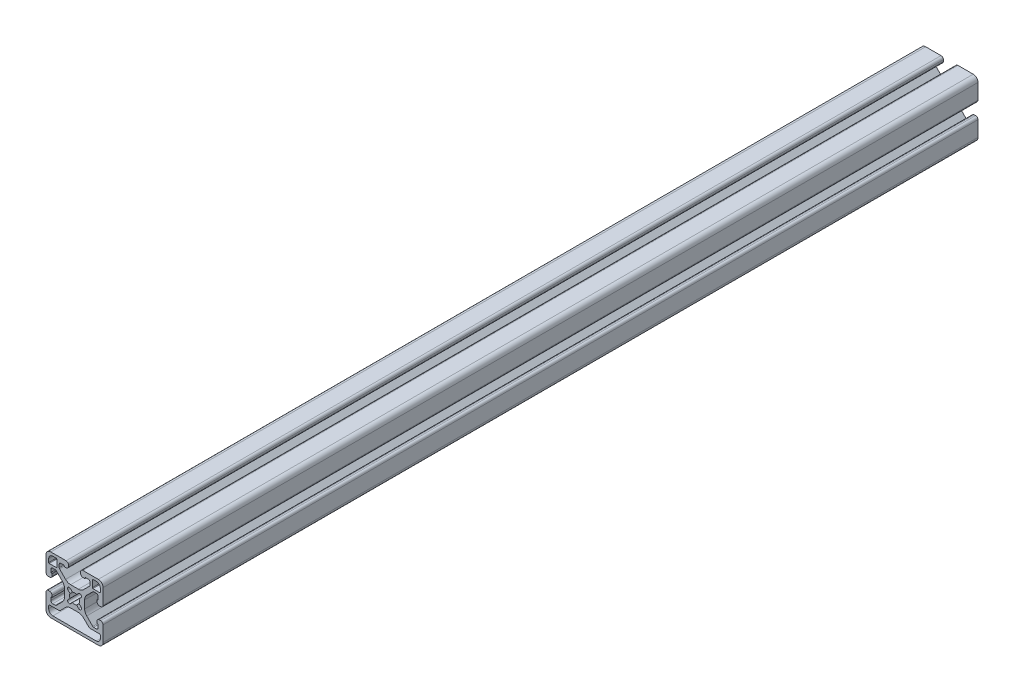
SolidWorks part; units mm, degrees
material "6105-T5 Aluminum"
ref_plane "Front Plane" through (0, 0, 0) normal (0, 0, 1) x (1, 0, 0)
ref_plane "Top Plane" through (0, 0, 0) normal (0, 1, 0) x (1, 0, 0)
ref_plane "Right Plane" through (0, 0, 0) normal (1, 0, 0) x (0, 0, -1)
sketch "Sketch1" plane through (0, 0, 0) normal (0, 0, 1) x (1, 0, 0)
  line L0 (-2.6153, -6.738) -> (2.6153, -6.738)
  line L1 (5.9739, -8.1292) -> (9.6866, -11.8418)
  line L2 (10.2254, -12.065) -> (16.51, -12.065)
  line L3 (17.272, -12.827) -> (17.272, -14.478)
  line L4 (14.478, -17.272) -> (-14.478, -17.272)
  line L5 (-17.272, -14.478) -> (-17.272, -12.827)
  line L6 (-16.51, -12.065) -> (-10.2254, -12.065)
  line L7 (-9.6866, -11.8418) -> (-5.9739, -8.1292)
  line L8 (16.8656, 11.8618) -> (12.2428, 11.8618)
  line L9 (11.8618, 12.2428) -> (11.8618, 16.8656)
  line L10 (12.2428, 17.2466) -> (14.4526, 17.2466)
  line L11 (17.2466, 14.4526) -> (17.2466, 12.2428)
  line L12 (-11.8618, 16.8656) -> (-11.8618, 12.2428)
  line L13 (-12.2428, 11.8618) -> (-16.8656, 11.8618)
  line L14 (-17.2466, 12.2428) -> (-17.2466, 14.4526)
  line L15 (-14.4526, 17.2466) -> (-12.2428, 17.2466)
  line L16 (1.4014, 3.0179) -> (2.7224, 4.3388)
  line L17 (4.3388, 2.7224) -> (3.0179, 1.4014)
  line L18 (3.0179, -1.4014) -> (4.3388, -2.7224)
  line L19 (2.7224, -4.3388) -> (1.4014, -3.0179)
  line L20 (-1.4014, -3.0179) -> (-2.7224, -4.3388)
  line L21 (-4.3388, -2.7224) -> (-3.0179, -1.4014)
  line L22 (-3.0179, 1.4014) -> (-4.3388, 2.7224)
  line L23 (-2.7224, 4.3388) -> (-1.4014, 3.0179)
  line L24 (-15.8242, 7.239) -> (-15.8242, 9.017)
  line L25 (-14.5542, 10.287) -> (-12.8105, 10.287)
  line L26 (-12.1819, 10.0266) -> (-8.1292, 5.9739)
  line L27 (-6.738, 2.6153) -> (-6.738, -2.6153)
  line L28 (-8.1292, -5.9739) -> (-12.1819, -10.0266)
  line L29 (-12.8105, -10.287) -> (-14.5542, -10.287)
  line L30 (-15.8242, -9.017) -> (-15.8242, -7.239)
  line L31 (-15.4432, -6.858) -> (-14.986, -6.858)
  line L32 (-14.986, -6.858) -> (-14.986, -5.6388)
  line L33 (-16.5608, -4.064) -> (-17.4752, -4.064)
  line L34 (-19.05, -5.6388) -> (-19.05, -15.875)
  line L35 (-15.875, -19.05) -> (15.875, -19.05)
  line L36 (19.05, -15.875) -> (19.05, -5.6388)
  line L37 (17.4752, -4.064) -> (16.5608, -4.064)
  line L38 (14.986, -5.6388) -> (14.986, -6.858)
  line L39 (14.986, -6.858) -> (15.4432, -6.858)
  line L40 (15.8242, -7.239) -> (15.8242, -9.017)
  line L41 (14.5542, -10.287) -> (12.8105, -10.287)
  line L42 (12.1819, -10.0266) -> (8.1292, -5.9739)
  line L43 (6.738, -2.6153) -> (6.738, 2.6153)
  line L44 (8.1292, 5.9739) -> (12.1819, 10.0266)
  line L45 (12.8105, 10.287) -> (14.5542, 10.287)
  line L46 (15.8242, 9.017) -> (15.8242, 7.239)
  line L47 (15.4432, 6.858) -> (14.986, 6.858)
  line L48 (14.986, 6.858) -> (14.986, 5.6388)
  line L49 (16.5608, 4.064) -> (17.4752, 4.064)
  line L50 (19.05, 5.6388) -> (19.05, 15.875)
  line L51 (15.875, 19.05) -> (5.6388, 19.05)
  line L52 (4.064, 17.4752) -> (4.064, 16.5608)
  line L53 (5.6388, 14.986) -> (6.858, 14.986)
  line L54 (6.858, 14.986) -> (6.858, 15.4432)
  line L55 (7.239, 15.8242) -> (9.017, 15.8242)
  line L56 (10.287, 14.5542) -> (10.287, 12.8105)
  line L57 (10.0266, 12.1819) -> (5.9739, 8.1292)
  line L58 (2.6153, 6.738) -> (-2.6153, 6.738)
  line L59 (-5.9739, 8.1292) -> (-10.0266, 12.1819)
  line L60 (-10.287, 12.8105) -> (-10.287, 14.5542)
  line L61 (-9.017, 15.8242) -> (-7.239, 15.8242)
  line L62 (-6.858, 15.4432) -> (-6.858, 14.986)
  line L63 (-6.858, 14.986) -> (-5.6388, 14.986)
  line L64 (-4.064, 16.5608) -> (-4.064, 17.4752)
  line L65 (-5.6388, 19.05) -> (-15.875, 19.05)
  line L66 (-19.05, 15.875) -> (-19.05, 5.6388)
  line L67 (-17.4752, 4.064) -> (-16.5608, 4.064)
  line L68 (-14.986, 5.6388) -> (-14.986, 6.858)
  line L69 (-14.986, 6.858) -> (-15.4432, 6.858)
  arc A0 (-2.6153, -6.738) -> (-5.9739, -8.1292) centre (-2.6153, -11.4878) ccw
  arc A1 (5.9739, -8.1292) -> (2.6153, -6.738) centre (2.6153, -11.4878) ccw
  arc A2 (9.6866, -11.8418) -> (10.2254, -12.065) centre (10.2254, -11.303) ccw
  arc A3 (17.272, -12.827) -> (16.51, -12.065) centre (16.51, -12.827) ccw
  arc A4 (14.478, -17.272) -> (17.272, -14.478) centre (14.478, -14.478) ccw
  arc A5 (-17.272, -14.478) -> (-14.478, -17.272) centre (-14.478, -14.478) ccw
  arc A6 (-16.51, -12.065) -> (-17.272, -12.827) centre (-16.51, -12.827) ccw
  arc A7 (-10.2254, -12.065) -> (-9.6866, -11.8418) centre (-10.2254, -11.303) ccw
  arc A8 (11.8618, 12.2428) -> (12.2428, 11.8618) centre (12.2428, 12.2428) ccw
  arc A9 (12.2428, 17.2466) -> (11.8618, 16.8656) centre (12.2428, 16.8656) ccw
  arc A10 (17.2466, 14.4526) -> (14.4526, 17.2466) centre (14.4526, 14.4526) ccw
  arc A11 (16.8656, 11.8618) -> (17.2466, 12.2428) centre (16.8656, 12.2428) ccw
  arc A12 (-12.2428, 11.8618) -> (-11.8618, 12.2428) centre (-12.2428, 12.2428) ccw
  arc A13 (-17.2466, 12.2428) -> (-16.8656, 11.8618) centre (-16.8656, 12.2428) ccw
  arc A14 (-14.4526, 17.2466) -> (-17.2466, 14.4526) centre (-14.4526, 14.4526) ccw
  arc A15 (-11.8618, 16.8656) -> (-12.2428, 17.2466) centre (-12.2428, 16.8656) ccw
  arc A16 (1.4014, 3.0179) -> (-1.4014, 3.0179) centre (0, 0) ccw
  arc A17 (4.3388, 2.7224) -> (2.7224, 4.3388) centre (3.5306, 3.5306) ccw
  arc A18 (3.0179, -1.4014) -> (3.0179, 1.4014) centre (0, 0) ccw
  arc A19 (2.7224, -4.3388) -> (4.3388, -2.7224) centre (3.5306, -3.5306) ccw
  arc A20 (-1.4014, -3.0179) -> (1.4014, -3.0179) centre (0, 0) ccw
  arc A21 (-4.3388, -2.7224) -> (-2.7224, -4.3388) centre (-3.5306, -3.5306) ccw
  arc A22 (-3.0179, 1.4014) -> (-3.0179, -1.4014) centre (0, 0) ccw
  arc A23 (-2.7224, 4.3388) -> (-4.3388, 2.7224) centre (-3.5306, 3.5306) ccw
  arc A24 (-15.8242, 7.239) -> (-15.4432, 6.858) centre (-15.4432, 7.239) ccw
  arc A25 (-14.5542, 10.287) -> (-15.8242, 9.017) centre (-14.5542, 9.017) ccw
  arc A26 (-12.1819, 10.0266) -> (-12.8105, 10.287) centre (-12.8105, 9.398) ccw
  arc A27 (-6.738, 2.6153) -> (-8.1292, 5.9739) centre (-11.4878, 2.6153) ccw
  arc A28 (-8.1292, -5.9739) -> (-6.738, -2.6153) centre (-11.4878, -2.6153) ccw
  arc A29 (-12.8105, -10.287) -> (-12.1819, -10.0266) centre (-12.8105, -9.398) ccw
  arc A30 (-15.8242, -9.017) -> (-14.5542, -10.287) centre (-14.5542, -9.017) ccw
  arc A31 (-15.4432, -6.858) -> (-15.8242, -7.239) centre (-15.4432, -7.239) ccw
  arc A32 (-14.986, -5.6388) -> (-16.5608, -4.064) centre (-16.5608, -5.6388) ccw
  arc A33 (-17.4752, -4.064) -> (-19.05, -5.6388) centre (-17.4752, -5.6388) ccw
  arc A34 (-19.05, -15.875) -> (-15.875, -19.05) centre (-15.875, -15.875) ccw
  arc A35 (15.875, -19.05) -> (19.05, -15.875) centre (15.875, -15.875) ccw
  arc A36 (19.05, -5.6388) -> (17.4752, -4.064) centre (17.4752, -5.6388) ccw
  arc A37 (16.5608, -4.064) -> (14.986, -5.6388) centre (16.5608, -5.6388) ccw
  arc A38 (15.8242, -7.239) -> (15.4432, -6.858) centre (15.4432, -7.239) ccw
  arc A39 (14.5542, -10.287) -> (15.8242, -9.017) centre (14.5542, -9.017) ccw
  arc A40 (12.1819, -10.0266) -> (12.8105, -10.287) centre (12.8105, -9.398) ccw
  arc A41 (6.738, -2.6153) -> (8.1292, -5.9739) centre (11.4878, -2.6153) ccw
  arc A42 (8.1292, 5.9739) -> (6.738, 2.6153) centre (11.4878, 2.6153) ccw
  arc A43 (12.8105, 10.287) -> (12.1819, 10.0266) centre (12.8105, 9.398) ccw
  arc A44 (15.8242, 9.017) -> (14.5542, 10.287) centre (14.5542, 9.017) ccw
  arc A45 (15.4432, 6.858) -> (15.8242, 7.239) centre (15.4432, 7.239) ccw
  arc A46 (14.986, 5.6388) -> (16.5608, 4.064) centre (16.5608, 5.6388) ccw
  arc A47 (17.4752, 4.064) -> (19.05, 5.6388) centre (17.4752, 5.6388) ccw
  arc A48 (19.05, 15.875) -> (15.875, 19.05) centre (15.875, 15.875) ccw
  arc A49 (5.6388, 19.05) -> (4.064, 17.4752) centre (5.6388, 17.4752) ccw
  arc A50 (4.064, 16.5608) -> (5.6388, 14.986) centre (5.6388, 16.5608) ccw
  arc A51 (7.239, 15.8242) -> (6.858, 15.4432) centre (7.239, 15.4432) ccw
  arc A52 (10.287, 14.5542) -> (9.017, 15.8242) centre (9.017, 14.5542) ccw
  arc A53 (10.0266, 12.1819) -> (10.287, 12.8105) centre (9.398, 12.8105) ccw
  arc A54 (2.6153, 6.738) -> (5.9739, 8.1292) centre (2.6153, 11.4878) ccw
  arc A55 (-5.9739, 8.1292) -> (-2.6153, 6.738) centre (-2.6153, 11.4878) ccw
  arc A56 (-10.287, 12.8105) -> (-10.0266, 12.1819) centre (-9.398, 12.8105) ccw
  arc A57 (-9.017, 15.8242) -> (-10.287, 14.5542) centre (-9.017, 14.5542) ccw
  arc A58 (-6.858, 15.4432) -> (-7.239, 15.8242) centre (-7.239, 15.4432) ccw
  arc A59 (-5.6388, 14.986) -> (-4.064, 16.5608) centre (-5.6388, 16.5608) ccw
  arc A60 (-4.064, 17.4752) -> (-5.6388, 19.05) centre (-5.6388, 17.4752) ccw
  arc A61 (-15.875, 19.05) -> (-19.05, 15.875) centre (-15.875, 15.875) ccw
  arc A62 (-19.05, 5.6388) -> (-17.4752, 4.064) centre (-17.4752, 5.6388) ccw
  arc A63 (-16.5608, 4.064) -> (-14.986, 5.6388) centre (-16.5608, 5.6388) ccw
extrude "Extrude1" add sketch "Sketch1" against normal mid plane 584.2
hole_wizard "7060-LEFT" positions "Sketch3" profile "Sketch2" tap size "5/16-18" standard "Ansi Inch"
sketch "Sketch3" plane through (0, 0, 292.1) normal (0, 0, 1) x (1, 0, 0)
  point P1 (0, 0)
sketch "Sketch2" plane through (0, 0, 292.1) normal (1, 0, 0) x (0, -1, 0)
  line L0 (0, 0) -> (0, 22.1161)
  line L1 (0, 22.1161) -> (3.3274, 20.1168)
  line L2 (3.3274, 20.1168) -> (3.3274, 0)
  line L5 (3.3274, 0) -> (0, 0)
  line L10 (0, 22.1161) -> (-3.3274, 20.1168) construction
  line L11 (0, -6.35) -> (0, 107.95) construction
  dimension "Tap Drill Dia." = 6.6548
  dimension "Tap Drill Depth" = 20.1168
  dimension "Drill Angle" = 118
hole_wizard "7060-RIGHT" positions "Sketch5" profile "Sketch4" tap size "5/16-18" standard "Ansi Inch"
sketch "Sketch5" plane through (0, 0, -292.1) normal (0, 0, -1) x (-1, 0, 0)
  point P1 (0, 0)
sketch "Sketch4" plane through (0, 0, -292.1) normal (1, 0, 0) x (0, 1, 0)
  line L0 (0, 0) -> (0, 22.1161)
  line L1 (0, 22.1161) -> (3.3274, 20.1168)
  line L2 (3.3274, 20.1168) -> (3.3274, 0)
  line L5 (3.3274, 0) -> (0, 0)
  line L10 (0, 22.1161) -> (-3.3274, 20.1168) construction
  line L11 (0, -6.35) -> (0, 107.95) construction
  dimension "Tap Drill Dia." = 6.6548
  dimension "Tap Drill Depth" = 20.1168
  dimension "Drill Angle" = 118
